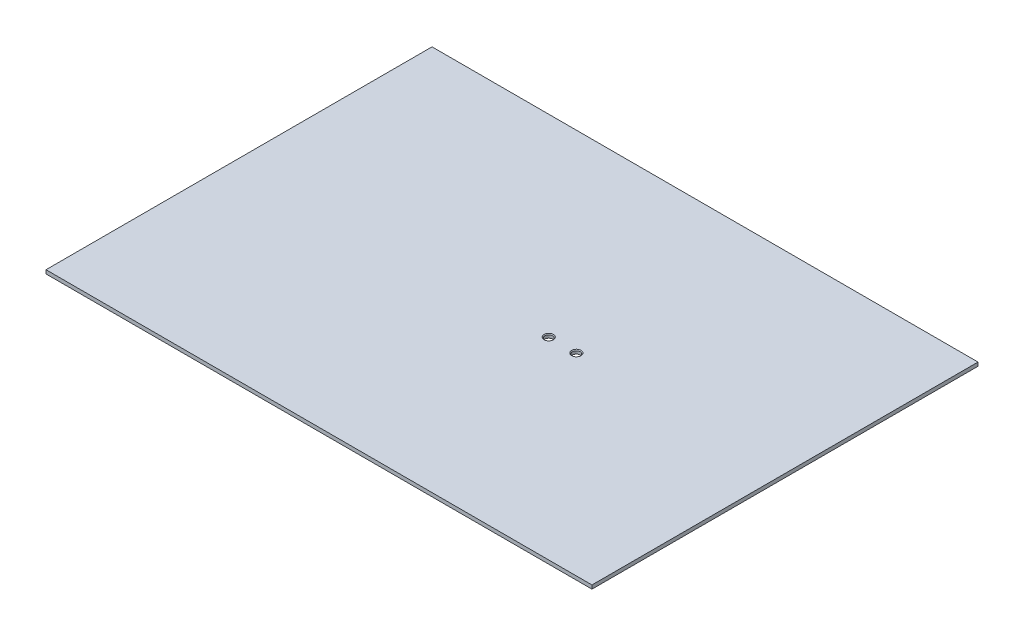
SolidWorks part; units mm, degrees
ref_plane "Front Plane" through (0, 0, 0) normal (0, 0, 1) x (1, 0, 0)
ref_plane "Top Plane" through (0, 0, 0) normal (0, 1, 0) x (1, 0, 0)
ref_plane "Right Plane" through (0, 0, 0) normal (1, 0, 0) x (0, 0, -1)
sketch "Sketch1" plane through (0, 0, 0) normal (0, 1, 0) x (1, 0, 0)
  line L1 (-148.5, -105) -> (148.5, -105)
  line L2 (-148.5, -105) -> (-148.5, 105)
  line L3 (-148.5, 105) -> (148.5, 105)
  line L4 (148.5, -105) -> (148.5, 105)
  line L5 (-148.5, -105) -> (148.5, 105) construction
  line L6 (-148.5, 105) -> (148.5, -105) construction
  point P0 (0, 0)
  dimension "D1" = 297
  dimension "D2" = 210
extrude "Boss-Extrude1" add sketch "Sketch1" along normal blind 2 contours L3 L4 L1 L2
sketch "Sketch4" plane through (0, 2, 0) normal (0, 1, 0) x (1, 0, 0)
  line L0 (0, 0) -> (148.5, 0) construction
  line L1 (148.5, -105) -> (148.5, 105) construction
  line L2 (0, -1.1) -> (0, 1.1) construction
  line L3 (-40, -6.35) -> (40, -6.35) construction
  line L4 (-40, -6.35) -> (-40, 6.35) construction
  line L5 (-40, 6.35) -> (40, 6.35) construction
  line L6 (40, -6.35) -> (40, 6.35) construction
  line L7 (-40, -6.35) -> (40, 6.35) construction
  line L8 (-40, 6.35) -> (40, -6.35) construction
  line L9 (15, -6.35) -> (40, -6.35)
  line L10 (15, -6.35) -> (15, 6.35)
  line L11 (15, 6.35) -> (40, 6.35)
  line L12 (40, -6.35) -> (40, 6.35)
  line L13 (15, -6.35) -> (40, 6.35) construction
  line L14 (15, 6.35) -> (40, -6.35) construction
  line L15 (-15, -6.35) -> (-40, -6.35)
  line L16 (-40, -6.35) -> (-40, 6.35)
  line L17 (-15, 6.35) -> (-40, 6.35)
  point P5 (0, 0)
  point P10 (27.5, 0)
  point P19 (35, 0)
  point P20 (20, 0)
  dimension "D1" = 12.7
  dimension "D2" = 80
  dimension "D3" = 5
  dimension "D4" = 5
  dimension "D5" = 20
sketch "Sketch2" plane through (0, 2, 0) normal (0, 1, 0) x (1, 0, 0)
  line L2 (0, -1.1) -> (0, 1.1) construction
  line L4 (-40, 6.35) -> (40, 6.35) construction
  line L5 (-40, 6.35) -> (-40, -6.35) construction
  line L6 (-40, -6.35) -> (40, -6.35) construction
  line L7 (40, 6.35) -> (40, -6.35) construction
  line L8 (-40, 6.35) -> (40, -6.35) construction
  line L9 (-40, -6.35) -> (40, 6.35) construction
  line L10 (0, 0) -> (148.5, 0) construction
  line L11 (148.5, -105) -> (148.5, 105) construction
  line L13 (0, 0) -> (-148.5, 0) construction
  line L14 (-148.5, -105) -> (-148.5, 105) construction
  line L22 (-40, -6.35) -> (-40, 6.35) construction
  line L23 (0, 0) -> (148.5, 0) construction
  line L24 (40, -6.35) -> (40, 6.35) construction
  point P5 (35, 0)
  point P6 (20, 0)
  point P10 (0, 0)
  point P13 (0, 0)
  dimension "D1" = 5
  dimension "D2" = 20
  dimension "D4" = 12.7
hole_wizard "M5 Tapped Hole1" positions "Sketch2" profile "Sketch3" tap size "M5" standard "ISO"
sketch "Sketch3" plane through (20, 2, 0) normal (1, 0, 0) x (0, 0, 1)
  line L0 (0, 0) -> (0, 2)
  line L1 (0, 2) -> (2.1, 2)
  line L2 (2.1, 2) -> (2.1, 0.425)
  line L3 (2.1, 0.425) -> (2.525, 0)
  line L5 (2.525, 0) -> (0, 0)
  line L6 (-2.1, 0.425) -> (-2.525, 0) construction
  line L11 (0, -6.35) -> (0, 107.95) construction
  dimension "Thru Tap Drill Dia." = 4.2
  dimension "Thru Tap Drill Depth" = 2
  dimension "Near C'Sink Dia." = 5.05
  dimension "Near C'Sink Angle" = 90
cosmetic thread "Hole Thread3" parameters "D2"=5
cosmetic thread "Hole Thread4" parameters "D2"=5
equation "\"l\"= 297"
equation "\"w\"= 210mm"
equation "\"D1@Sketch1\"=\"l\""
equation "\"D2@Sketch1\"=\"w\""
